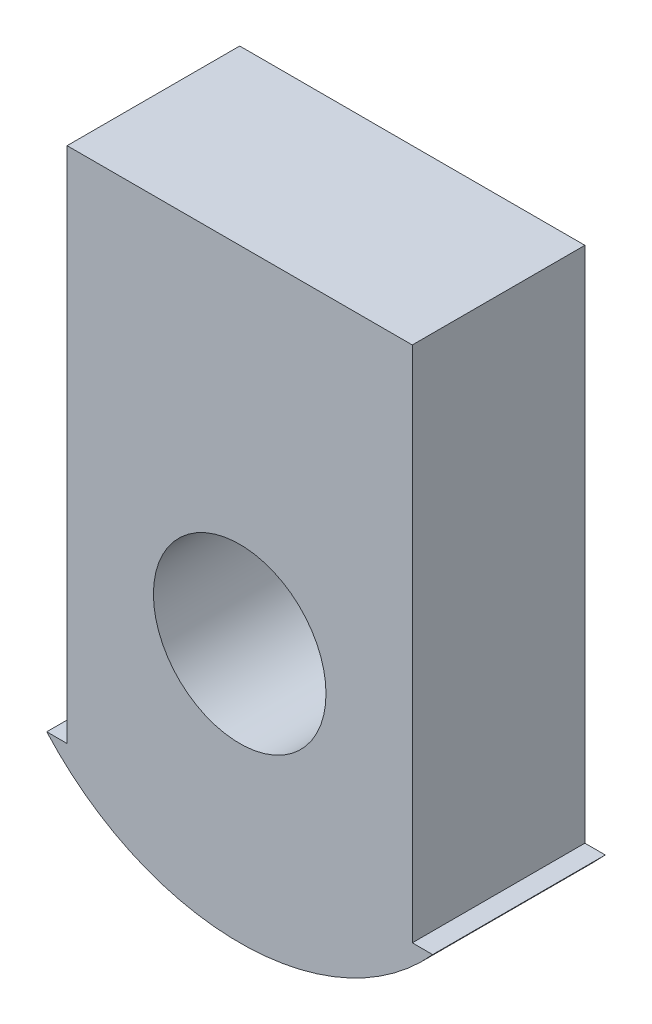
SolidWorks part; units mm, degrees
ref_plane "Alzado" through (0, 0, 0) normal (0, 0, 1) x (1, 0, 0)
ref_plane "Planta" through (0, 0, 0) normal (0, 1, 0) x (1, 0, 0)
ref_plane "Vista lateral" through (0, 0, 0) normal (1, 0, 0) x (0, 0, -1)
sketch "Croquis1" plane through (0, 0, 0) normal (0, 0, 1) x (1, 0, 0)
  line L1 (5, -5) -> (5.5902, -5)
  line L2 (-5, -5) -> (-5, 5)
  line L4 (5, -5) -> (5, 5)
  line L5 (-5, -5) -> (5, 5) construction
  line L6 (-5, 5) -> (5, -5) construction
  line L7 (-5, 5) -> (-5, 10)
  line L8 (-5.5902, -5) -> (-5, -5)
  line L9 (-5, 10) -> (5, 10)
  line L10 (5, 5) -> (5, 10)
  arc A0 (-5.5902, -5) -> (5.5902, -5) centre (0, 0) ccw
  circle A2 centre (0, 0) radius 2.5
  dimension "D2" = 15
  dimension "D4" = 5
  dimension "D1" = 10
  dimension "D3" = 10
  dimension "D5" = 5
extrude "Saliente-Extruir1" add sketch "Croquis1" along normal blind 5
